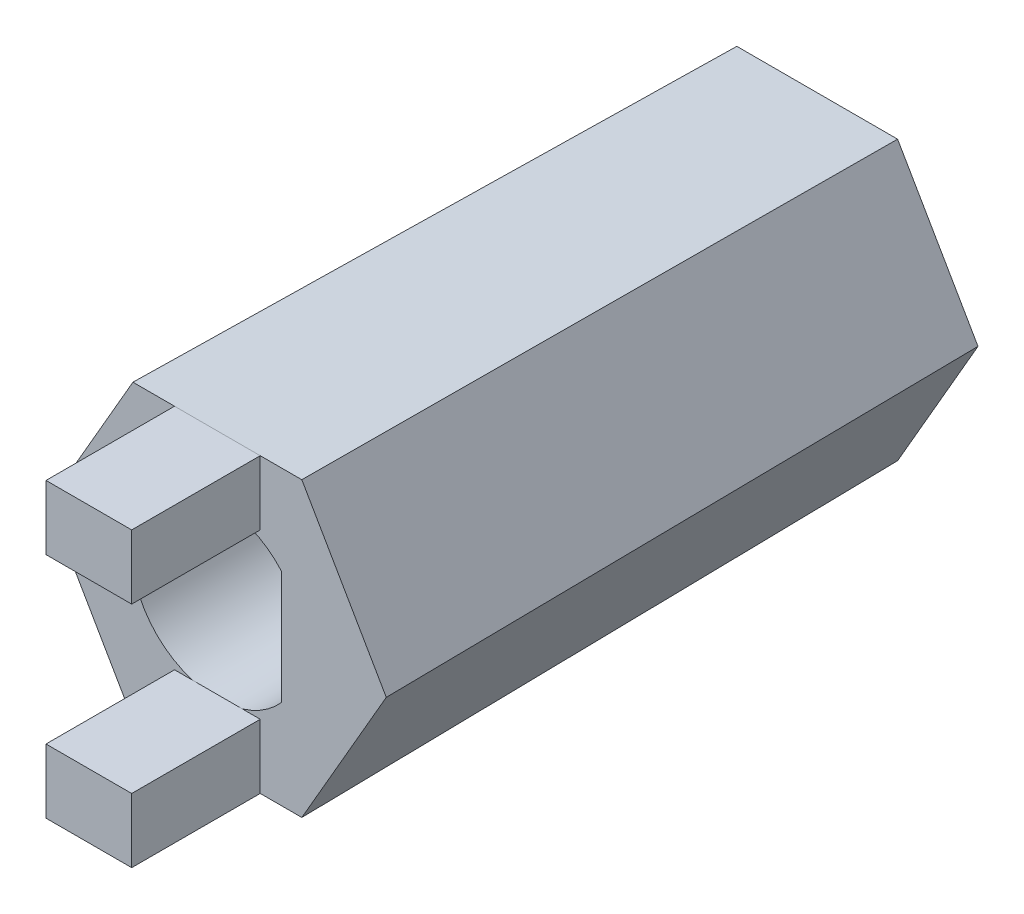
SolidWorks part; units mm, degrees
ref_plane "前视基准面" through (0, 0, 0) normal (0, 0, 1) x (1, 0, 0)
ref_plane "上视基准面" through (0, 0, 0) normal (0, 1, 0) x (1, 0, 0)
ref_plane "右视基准面" through (0, 0, 0) normal (1, 0, 0) x (0, 0, -1)
sketch "草图1" plane through (0, 0, 0) normal (0, 0, 1) x (1, 0, 0)
  line L1 (1.8764, 3.25) -> (-1.8764, 3.25)
  line L2 (-1.8764, 3.25) -> (-3.7528, 0)
  line L3 (-3.7528, 0) -> (-1.8764, -3.25)
  line L4 (-1.8764, -3.25) -> (1.8764, -3.25)
  line L5 (1.8764, -3.25) -> (3.7528, 0)
  line L6 (3.7528, 0) -> (1.8764, 3.25)
  circle A0 centre (0, 0) radius 3.25 construction
  dimension "D1" = 6.5
extrude "凸台-拉伸1" add sketch "草图1" along normal blind 14 draft 0.67 draft outward yes
sketch "草图2" plane through (0, 0, 14) normal (0, 0, 1) x (1, 0, 0)
  line L0 (1.5, 1.3229) -> (1.5, -1.3229)
  circle A0 centre (0, 0) radius 2
  dimension "D1" = 4
  dimension "D2" = 1.5
extrude "切除-拉伸1" cut sketch "草图2" against normal blind 7 draft 0.67 contours L0 A0
sketch "草图3" plane through (0, 0, 14) normal (0, 0, 1) x (1, 0, 0)
  line L0 (0, 0) -> (0, 2.7554) construction
  line L1 (0, 0) -> (3.2216, 0) construction
  line L2 (1.9709, 3.4137) -> (-1.9709, 3.4137) construction
  line L3 (1, 1.9137) -> (-1, 1.9137)
  line L4 (1, 1.9137) -> (1, 3.4137)
  line L5 (1, 3.4137) -> (-1, 3.4137)
  line L6 (-1, 1.9137) -> (-1, 3.4137)
  line L7 (1, 1.9137) -> (-1, 3.4137) construction
  line L8 (1, 3.4137) -> (-1, 1.9137) construction
  line L9 (1, -3.4137) -> (-1, -3.4137)
  line L10 (-1, -1.9137) -> (-1, -3.4137)
  line L11 (1, -1.9137) -> (-1, -1.9137)
  line L12 (1, -1.9137) -> (1, -3.4137)
  point P3 (0, 2.6637)
  dimension "D1" = 1.5
  dimension "D2" = 2
extrude "凸台-拉伸2" add sketch "草图3" along normal blind 3
